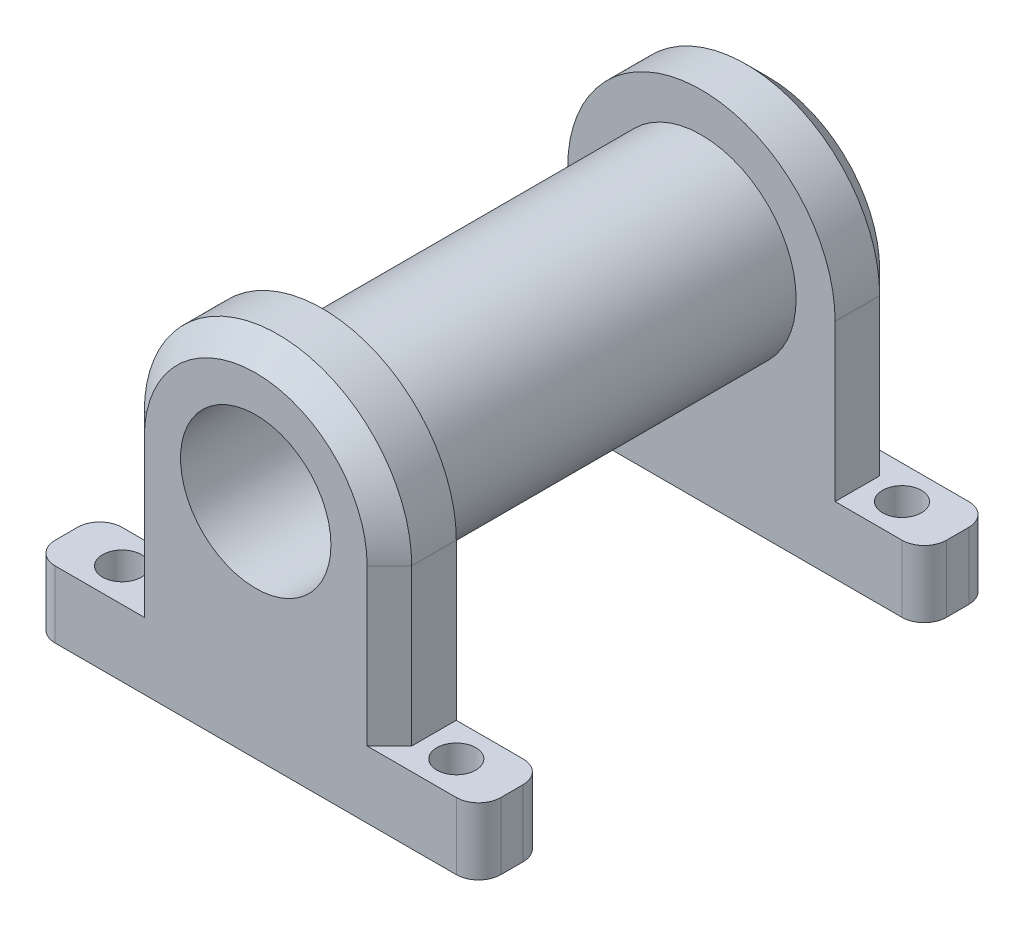
SolidWorks part; units mm, degrees
ref_plane "Front Plane" through (0, 0, 0) normal (0, 0, 1) x (1, 0, 0)
ref_plane "Top Plane" through (0, 0, 0) normal (0, 1, 0) x (1, 0, 0)
ref_plane "Right Plane" through (0, 0, 0) normal (1, 0, 0) x (0, 0, -1)
sketch "Sketch1" plane through (0, 0, 0) normal (0, 0, 1) x (1, 0, 0)
  line L0 (-12, 0) -> (-12, -14)
  line L1 (-12, -20) -> (12, -20)
  line L2 (12, -14) -> (12, 0)
  line L3 (-12, -14) -> (12, -14) construction
  line L4 (-12, -20) -> (-20, -20)
  line L6 (-12, -14) -> (-20, -14)
  line L7 (-20, -20) -> (-20, -14)
  line L8 (12, -20) -> (20, -20)
  line L10 (12, -14) -> (20, -14)
  line L11 (20, -20) -> (20, -14)
  line L12 (0, -20) -> (0, -14) construction
  line L13 (12, -14) -> (12, -20) construction
  line L14 (-12, -14) -> (-12, -20) construction
  arc A0 (12, 0) -> (-12, 0) centre (0, 0) ccw
  dimension "D1" = 24
  dimension "D2" = 20
  dimension "D3" = 8
  dimension "D4" = 6
extrude "Boss-Extrude1" add sketch "Sketch1" along normal blind 6
sketch "Sketch2" plane through (0, 0, 6) normal (0, 0, 1) x (1, 0, 0)
  circle A0 centre (0, 0) radius 8.5
  dimension "D1" = 17
extrude "Boss-Extrude2" add sketch "Sketch2" along normal blind 34
sketch "Sketch3" plane through (0, 0, 40) normal (0, 0, 1) x (1, 0, 0)
  line L3 (-12, 0) -> (-12, -14)
  line L4 (-20, -20) -> (20, -20)
  line L5 (12, -14) -> (12, 0)
  line L6 (-12, 0) -> (-12, -14)
  line L7 (-20, -20) -> (20, -20)
  line L8 (12, -14) -> (12, 0)
  line L13 (-20, -14) -> (-20, -20)
  line L14 (-20, -14) -> (-20, -20)
  line L15 (20, -20) -> (20, -14)
  line L16 (20, -20) -> (20, -14)
  line L17 (20, -14) -> (12, -14)
  line L18 (20, -14) -> (12, -14)
  line L19 (-12, -14) -> (-20, -14)
  line L20 (-12, -14) -> (-20, -14)
  arc A2 (12, 0) -> (-12, 0) centre (0, 0) ccw
  arc A3 (12, 0) -> (-12, 0) centre (0, 0) ccw
  dimension "D1" = 0
extrude "Boss-Extrude3" add sketch "Sketch3" along normal blind 6
sketch "Sketch4" plane through (0, 0, 46) normal (0, 0, 1) x (1, 0, 0)
  circle A0 centre (0, 0) radius 6.75
  dimension "D1" = 13.5
extrude "Cut-Extrude1" cut sketch "Sketch4" against normal through all
sketch "Sketch5" plane through (0, -20, 0) normal (0, -1, 0) x (1, 0, 0)
  line L0 (-5, 43) -> (-12, 43) construction
  line L1 (-5, 43) -> (5, 43) construction
  line L2 (-5, 43) -> (-5, 3) construction
  line L3 (-5, 3) -> (5, 3) construction
  line L4 (5, 43) -> (5, 3) construction
  line L5 (-12, 46) -> (-12, 40) construction
  line L6 (-5, 3) -> (-12, 3) construction
  line L7 (-12, 6) -> (-12, 0) construction
  line L8 (0, 3) -> (0, 0) construction
  circle A0 centre (-5, 43) radius 2.25
  circle A1 centre (5, 43) radius 2.25
  circle A2 centre (-5, 3) radius 2.25
  circle A3 centre (5, 3) radius 2.25
  dimension "D3" = 4.5
  dimension "D1" = 10
  dimension "D2" = 40
extrude "Cut-Extrude2" cut sketch "Sketch5" against normal blind 13
sketch "Sketch9" plane through (0, -14, 0) normal (0, 1, 0) x (1, 0, 0)
  line L0 (-15, -3) -> (15, -3) construction
  line L1 (15, -3) -> (15, -43) construction
  line L2 (15, -43) -> (-15, -43) construction
  line L3 (-15, -43) -> (-15, -3) construction
  line L4 (0, 0) -> (0, -3) construction
  line L5 (0, -3) -> (0, -43) construction
  line L6 (12, 0) -> (-12, 0) construction
  line L7 (-12, -46) -> (-20, -46) construction
  circle A0 centre (15, -43) radius 1.75
  circle A1 centre (-15, -43) radius 1.75
  circle A2 centre (15, -3) radius 1.75
  circle A3 centre (-15, -3) radius 1.75
  dimension "D4" = 3.5
  dimension "D1" = 30
  dimension "D2" = 3
  dimension "D3" = 3
extrude "Cut-Extrude5" cut sketch "Sketch9" against normal through all
fillet "Fillet1" radius 2 8 edges at (-20, -17, 0) (-20, -17, 40) (-20, -17, 6) (-20, -17, 46) (20, -17, 46) (20, -17, 40) (20, -17, 6) (20, -17, 0)
chamfer "Chamfer4" distance 2 angle 45 6 edges at (12, -7, 0) (-12, -7, 0) (0, 12, 0) (12, -7, 46) (0, 12, 46) (-12, -7, 46)
